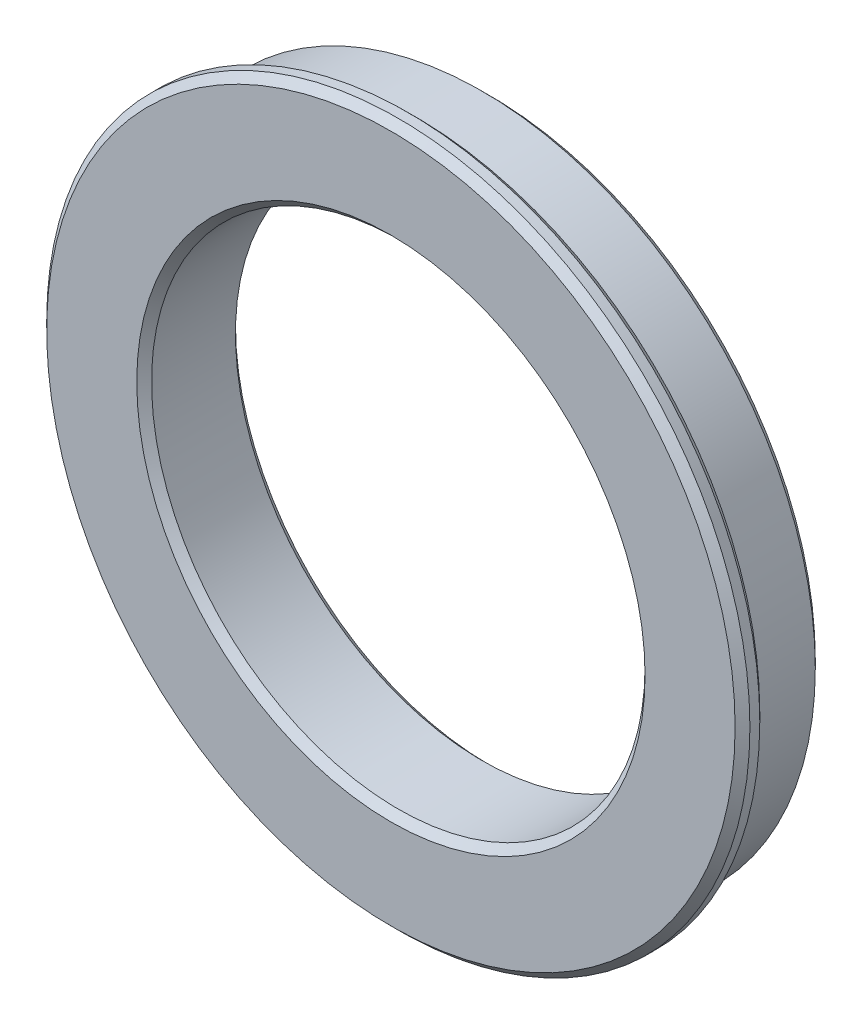
SolidWorks part; units mm, degrees
ref_plane "前视基准面" through (0, 0, 0) normal (0, 0, 1) x (1, 0, 0)
ref_plane "上视基准面" through (0, 0, 0) normal (0, 1, 0) x (1, 0, 0)
ref_plane "右视基准面" through (0, 0, 0) normal (1, 0, 0) x (0, 0, -1)
sketch "草图1" plane through (0, 0, 0) normal (0, 0, 1) x (1, 0, 0)
  circle A0 centre (0, 0) radius 13.5
  circle A1 centre (0, 0) radius 10
  dimension "D1" = 20
  dimension "D2" = 27
extrude "凸台-拉伸1" add sketch "草图1" along normal mid plane 4
sketch "草图2" plane through (0, 0, 2) normal (0, 0, 1) x (1, 0, 0)
  circle A0 centre (0, 0) radius 14.25
  circle A1 centre (0, 0) radius 10 construction
  circle A2 centre (0, 0) radius 10
  dimension "D1" = 28.5
extrude "凸台-拉伸2" add sketch "草图2" against normal blind 1
chamfer "倒角1" distance 0.3 angle 45 5 edges at (10, 0, 2) (14.25, 0, 1) (14.25, 0, 2) (10, 0, -2) (13.5, 0, -2)
